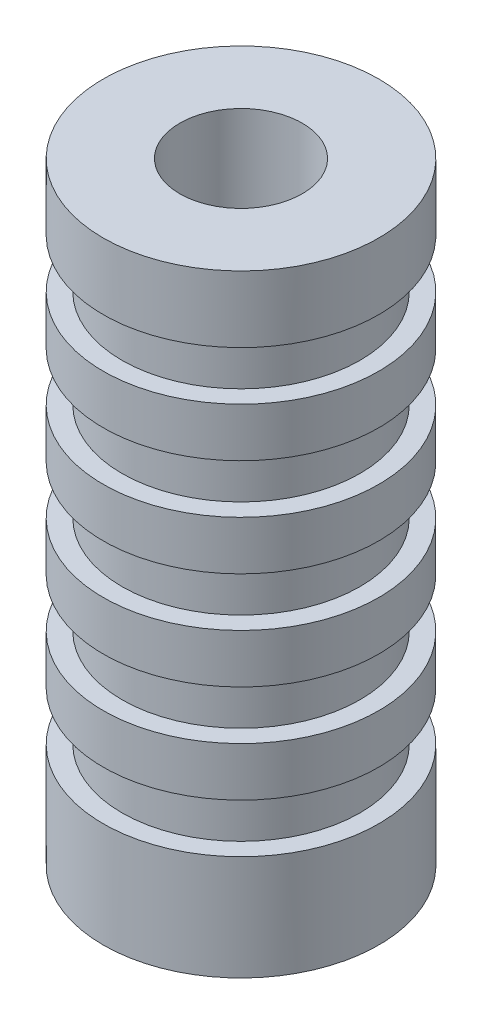
SolidWorks part; units mm, degrees
ref_plane "Front Plane" through (0, 0, 0) normal (0, 0, 1) x (1, 0, 0)
ref_plane "Top Plane" through (0, 0, 0) normal (0, 1, 0) x (1, 0, 0)
ref_plane "Right Plane" through (0, 0, 0) normal (1, 0, 0) x (0, 0, -1)
sketch "Sketch1" plane through (0, 0, 0) normal (0, 1, 0) x (1, 0, 0)
  circle A0 centre (0, 0) radius 2.54
  circle A1 centre (0, 0) radius 5.715
  dimension "D1" = 5.08
extrude "Boss-Extrude1" add sketch "Sketch1" along normal blind 25.4
sketch "Sketch2" [suppressed] plane through (0, 0, 0) normal (0, 1, 0) x (1, 0, 0)
  circle A0 centre (0, 0) radius 3.175
sketch "Sketch3" plane through (0, 0, 0) normal (1, 0, 0) x (0, 0, -1)
  line L0 (5.715, 4.3574) -> (5.715, 6.3894)
  line L2 (4.9352, 4.3574) -> (4.9352, 6.3894)
  line L3 (4.9352, 4.3574) -> (5.715, 4.3574)
  line L4 (5.715, 0) -> (5.715, 25.4) construction
  line L5 (5.715, 8.4214) -> (5.715, 10.4534)
  line L6 (5.715, 0) -> (5.715, 25.4) construction
  line L7 (5.715, 6.3894) -> (4.9352, 6.3894)
  line L8 (4.9352, 8.4214) -> (4.9352, 10.4534)
  line L9 (4.9352, 8.4214) -> (5.715, 8.4214)
  line L10 (5.715, 0) -> (5.715, 25.4) construction
  line L11 (5.715, 12.4854) -> (5.715, 14.5174)
  line L12 (5.715, 0) -> (5.715, 25.4) construction
  line L13 (5.715, 10.4534) -> (4.9352, 10.4534)
  line L14 (4.9352, 12.4854) -> (4.9352, 14.5174)
  line L15 (4.9352, 12.4854) -> (5.715, 12.4854)
  line L16 (5.715, 0) -> (5.715, 25.4) construction
  line L17 (5.715, 16.5494) -> (5.715, 18.5814)
  line L18 (5.715, 0) -> (5.715, 25.4) construction
  line L19 (5.715, 14.5174) -> (4.9352, 14.5174)
  line L20 (4.9352, 16.5494) -> (4.9352, 18.5814)
  line L21 (4.9352, 16.5494) -> (5.715, 16.5494)
  line L22 (5.715, 0) -> (5.715, 25.4) construction
  line L23 (5.715, 20.6134) -> (5.715, 22.6454)
  line L24 (5.715, 0) -> (5.715, 25.4) construction
  line L25 (5.715, 18.5814) -> (4.9352, 18.5814)
  line L26 (4.9352, 20.6134) -> (4.9352, 22.6454)
  line L27 (4.9352, 20.6134) -> (5.715, 20.6134)
  line L28 (5.715, 0) -> (5.715, 25.4) construction
  line L30 (5.715, 0) -> (5.715, 25.4) construction
  line L31 (5.715, 22.6454) -> (4.9352, 22.6454)
  dimension "D1" = 2.032
  dimension "D2" = 2.032
  dimension "D3" = 2.032
  dimension "D4" = 2.032
  dimension "D5" = 2.032
  dimension "D6" = 2.032
  dimension "D7" = 2.032
  dimension "D9" = 2.032
  dimension "D10" = 2.032
sketch "Sketch4" [suppressed] plane through (0, 0, 0) normal (1, 0, 0) x (0, 0, -1)
  line L0 (0, 0) -> (0, 26.291) construction
revolve "Cut-Revolve2" cut sketch "Sketch3" angle 360 about L0
